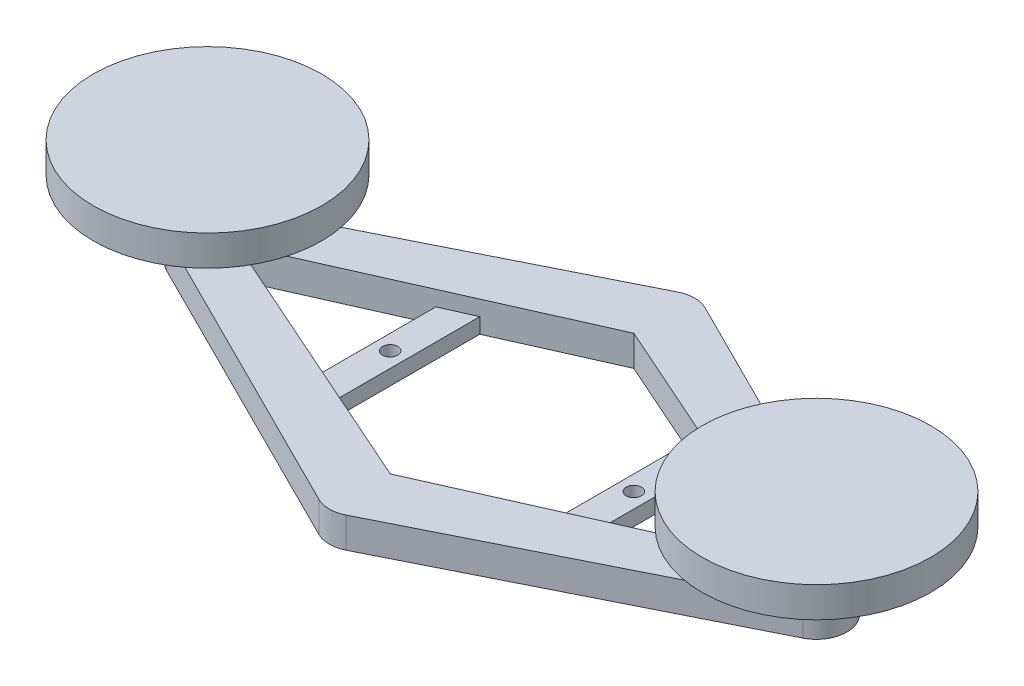
SolidWorks part; units mm, degrees
ref_plane "Front Plane" through (0, 0, 0) normal (0, 0, 1) x (1, 0, 0)
ref_plane "Top Plane" through (0, 0, 0) normal (0, 1, 0) x (1, 0, 0)
ref_plane "Right Plane" through (0, 0, 0) normal (1, 0, 0) x (0, 0, -1)
sketch "Sketch1" plane through (0, 0, 0) normal (0, 1, 0) x (1, 0, 0)
  line L0 (0, 0) -> (-50.8, 0)
  line L1 (0, 0) -> (50.8, 0)
  line L2 (0, 0) -> (0, 25.4)
  line L3 (0, 0) -> (0, -25.4)
  line L4 (-45.72, 0) -> (0, 20.32)
  line L5 (0, 20.32) -> (45.72, 0)
  line L6 (45.72, 0) -> (0, -20.32)
  line L7 (0, -20.32) -> (-45.72, 0)
  line L8 (-53.0718, -4.5437) -> (-2.2718, -29.9437)
  line L9 (-53.0718, 4.5437) -> (-2.2718, 29.9437)
  line L10 (2.2718, 29.9437) -> (53.0718, 4.5437)
  line L11 (53.0718, -4.5437) -> (2.2718, -29.9437)
  arc A0 (-53.0718, 4.5437) -> (-53.0718, -4.5437) centre (-50.8, 0) ccw
  arc A1 (2.2718, 29.9437) -> (-2.2718, 29.9437) centre (0, 25.4) ccw
  arc A2 (53.0718, -4.5437) -> (53.0718, 4.5437) centre (50.8, 0) ccw
  arc A3 (-2.2718, -29.9437) -> (2.2718, -29.9437) centre (0, -25.4) ccw
  dimension "D1" = 10.16
  dimension "D2" = 10.16
  dimension "D3" = 10.16
  dimension "D4" = 10.16
  dimension "D5" = 50.8
  dimension "D6" = 50.8
  dimension "D7" = 25.4
  dimension "D8" = 25.4
sketch "Sketch4" plane through (0, 0, 0) normal (0, 1, 0) x (1, 0, 0)
  line L0 (-22.86, 10.16) -> (-22.86, -10.16)
  line L1 (-45.72, 0) -> (0, 20.32) construction
  line L2 (0, -20.32) -> (-45.72, 0) construction
  line L3 (-22.86, 0) -> (-17.78, 0)
  line L4 (0, 0) -> (-50.8, 0) construction
  line L5 (-17.78, 0) -> (-17.78, 12.4178)
  line L6 (-17.78, 12.4178) -> (-17.78, -12.4178)
  line L7 (-22.86, 10.16) -> (-17.78, 12.4178)
  line L8 (-22.86, -10.16) -> (-17.78, -12.4178)
  line L9 (0, 20.32) -> (0, -20.32)
  line L10 (22.86, 10.16) -> (17.78, 12.4178)
  line L11 (22.86, 10.16) -> (22.86, -10.16)
  line L12 (22.86, -10.16) -> (17.78, -12.4178)
  line L13 (17.78, 12.4178) -> (17.78, -12.4178)
  circle A0 centre (-20.32, 0) radius 1.27
  circle A1 centre (20.32, 0) radius 1.27
sketch "Sketch5" plane through (0, 0, 0) normal (0, 1, 0) x (1, 0, 0)
  line L0 (-22.86, 10.16) -> (-22.86, -10.16)
  line L1 (-17.78, 12.4178) -> (-17.78, -12.4178)
  line L2 (-22.86, 10.16) -> (-17.78, 12.4178)
  line L3 (-22.86, -10.16) -> (-17.78, -12.4178)
  line L4 (22.86, 10.16) -> (17.78, 12.4178)
  line L5 (22.86, 10.16) -> (22.86, -10.16)
  line L6 (22.86, -10.16) -> (17.78, -12.4178)
  line L7 (17.78, 12.4178) -> (17.78, -12.4178)
  circle A0 centre (-20.32, 0) radius 1.27
  circle A1 centre (20.32, 0) radius 1.27
  point P2 (-22.86, 0)
extrude "Boss-Extrude2" add sketch "Sketch5" along normal blind 2.54
sketch "Sketch2" plane through (0, 0, 0) normal (0, 1, 0) x (1, 0, 0)
  line L0 (-45.72, 0) -> (0, 20.32)
  line L1 (0, 20.32) -> (45.72, 0)
  line L2 (45.72, 0) -> (0, -20.32)
  line L3 (0, -20.32) -> (-45.72, 0)
  line L4 (-53.0718, -4.5437) -> (-2.2718, -29.9437)
  line L5 (-53.0718, 4.5437) -> (-2.2718, 29.9437)
  line L6 (2.2718, 29.9437) -> (53.0718, 4.5437)
  line L7 (53.0718, -4.5437) -> (2.2718, -29.9437)
  arc A0 (-53.0718, 4.5437) -> (-53.0718, -4.5437) centre (-50.8, 0) ccw
  arc A1 (2.2718, 29.9437) -> (-2.2718, 29.9437) centre (0, 25.4) ccw
  arc A2 (53.0718, -4.5437) -> (53.0718, 4.5437) centre (50.8, 0) ccw
  arc A3 (-2.2718, -29.9437) -> (2.2718, -29.9437) centre (0, -25.4) ccw
extrude "Boss-Extrude1" add sketch "Sketch2" along normal blind 5.08
sketch "Sketch6" plane through (0, 5.08, 0) normal (0, 1, 0) x (1, 0, 0)
  circle A0 centre (-50.8, 0) radius 3.175
  circle A1 centre (50.8, 0) radius 3.175
extrude "Boss-Extrude3" add sketch "Sketch6" along normal blind 7.62
sketch "Sketch10" plane through (0, 12.7, 0) normal (0, 1, 0) x (1, 0, 0)
  circle A0 centre (-50.8, 0) radius 5.08
sketch "Sketch11" plane through (0, 12.7, 0) normal (0, 1, 0) x (1, 0, 0)
  circle A0 centre (-50.8, 0) radius 19.05
extrude "Boss-Extrude4" add sketch "Sketch11" along normal blind 5.08
sketch "Sketch12" plane through (0, 12.7, 0) normal (0, 1, 0) x (1, 0, 0)
  circle A0 centre (50.8, 0) radius 5.08
sketch "Sketch13" plane through (0, 12.7, 0) normal (0, 1, 0) x (1, 0, 0)
  circle A0 centre (50.8, 0) radius 19.05
extrude "Boss-Extrude5" add sketch "Sketch13" along normal blind 5.08
